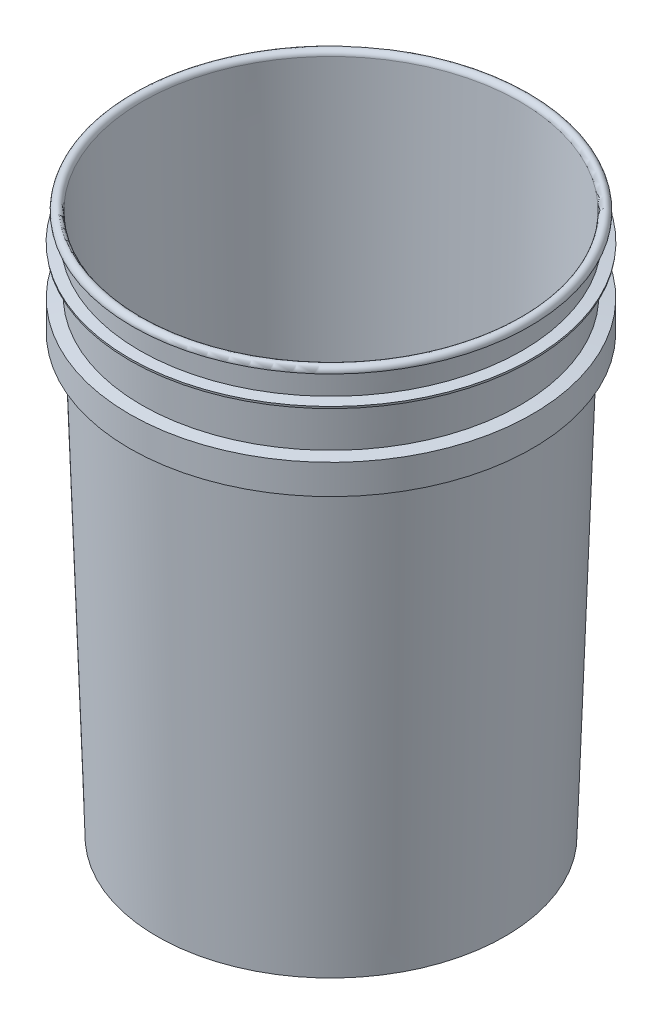
SolidWorks part; units mm, degrees
material "ABS"
ref_plane "Front Plane" through (0, 0, 0) normal (0, 0, 1) x (1, 0, 0)
ref_plane "Top Plane" through (0, 0, 0) normal (0, 1, 0) x (1, 0, 0)
ref_plane "Right Plane" through (0, 0, 0) normal (1, 0, 0) x (0, 0, -1)
other "Graphic1"
other "Graphic (Closed) -1"
sketch "Sketch1" plane through (0, 0, 0) normal (0, 0, 1) x (1, 0, 0)
  line L0 (0, -0.0942) -> (-1.0612, -0.0942)
  line L1 (-1.0612, -0.0942) -> (-1.0612, -0.2006)
  line L2 (-1.0612, -0.2006) -> (-1.1381, -0.2006)
  line L3 (-1.1381, -0.2006) -> (-1.1381, -0.0942)
  line L4 (-1.1381, -0.0942) -> (-5.3958, -0.0883)
  line L5 (-5.3958, -0.0883) -> (-5.3958, -0.2006)
  line L6 (-5.3958, -0.2006) -> (-5.4829, -0.2006)
  line L7 (-5.4829, -0.2006) -> (-5.9663, 14.4745)
  line L8 (-5.9663, 14.4745) -> (-6.2739, 14.4252)
  line L9 (-6.2739, 14.4252) -> (-6.2739, 13.5495)
  line L10 (-6.2739, 13.5495) -> (-6.3461, 13.5495)
  line L11 (-6.3461, 13.5495) -> (-6.3461, 14.4857)
  line L12 (-6.3461, 14.4857) -> (-5.9686, 14.5461)
  line L13 (-5.9686, 14.5461) -> (-6.0163, 15.9943)
  line L14 (-6.0163, 15.9943) -> (-6.3406, 15.9475)
  line L15 (-6.3406, 15.9475) -> (-6.3501, 16.0132)
  line L16 (-6.3501, 16.0132) -> (-6.0255, 16.0601)
  line L17 (-6.0255, 16.0601) -> (-6.0483, 16.8619)
  line L18 (-6.216, 16.833) -> (-6.2569, 16.833)
  line L19 (-5.9544, 16.8663) -> (-5.3991, 0.0069)
  line L20 (-5.3991, 0.0069) -> (0, 0)
  line L21 (0, 0) -> (0, -0.0942)
  line L22 (0, 0) -> (0, 9.7639) construction
  arc A0 (-6.0483, 16.8619) -> (-6.216, 16.833) centre (-6.1199, 16.7764) ccw
  arc A1 (-6.2569, 16.833) -> (-5.9544, 16.8663) centre (-6.1066, 16.8585) cw
  point P28 (0, 9.7639)
  dimension "D1" = 0.0665
revolve "Revolve1" add sketch "Sketch1" angle 360 about L22
scale "Scale1" bodies to scale 101 scale about centroid uniform scaling yes scale factor 24.694444
